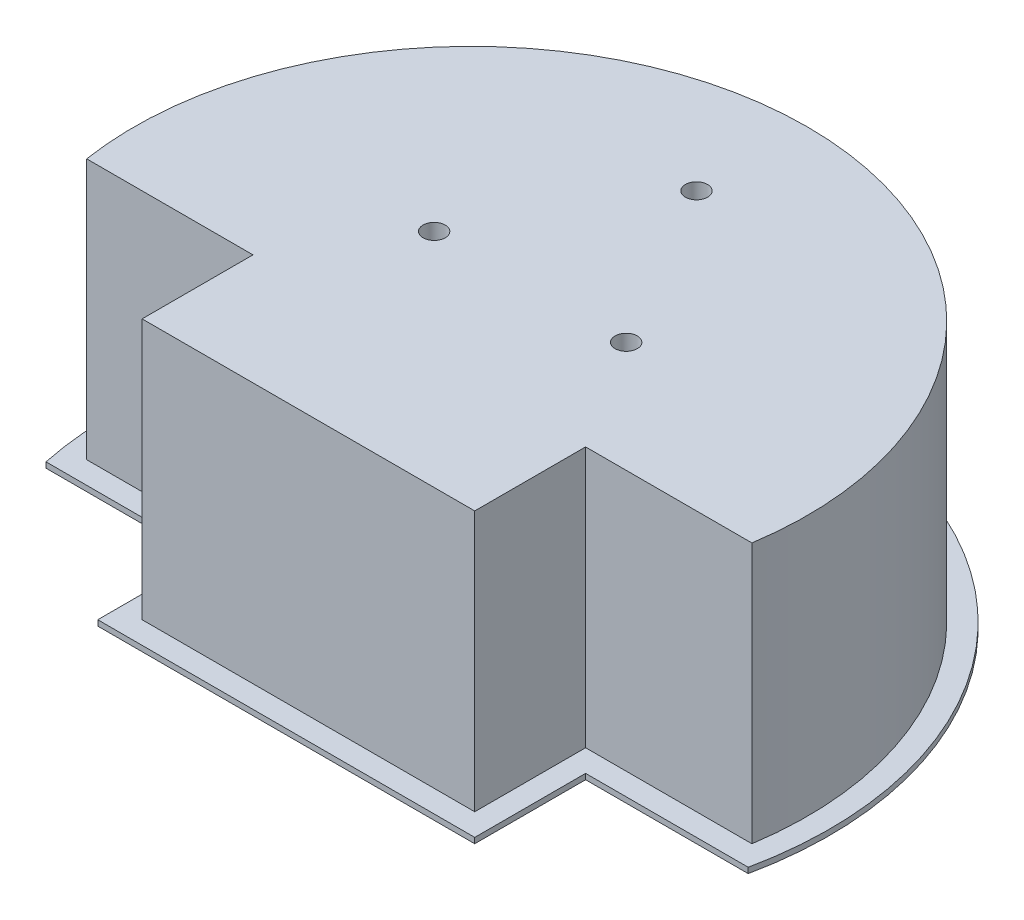
SolidWorks part; units mm, degrees
ref_plane "Alzado" through (0, 0, 0) normal (0, 0, 1) x (1, 0, 0)
ref_plane "Planta" through (0, 0, 0) normal (0, 1, 0) x (1, 0, 0)
ref_plane "Vista lateral" through (0, 0, 0) normal (1, 0, 0) x (0, 0, -1)
sketch "Croquis1" plane through (0, 0, 0) normal (0, 1, 0) x (1, 0, 0)
  line L0 (0, 0) -> (0, 36.4718) construction
  line L1 (-15, 0) -> (15, 0)
  line L2 (-15, 0) -> (-15, 10)
  line L3 (15, 0) -> (15, 10)
  line L4 (-15, 10) -> (-30, 10)
  line L5 (15, 10) -> (30, 10)
  arc A0 (-30, 10) -> (30, 10) centre (0, 14.6429) cw
  point P10 (0, 45)
  dimension "D4" = 35
  dimension "D1" = 30
  dimension "D2" = 10
  dimension "D3" = 15
extrude "Extruir-Lámina1" add sketch "Croquis1" along normal blind 20 thin thin type one direction reverse wall 2
sketch "Croquis2" plane through (0, 20, 0) normal (0, 1, 0) x (1, 0, 0)
  line L0 (15, 10) -> (30, 10) construction
  line L1 (15, 0) -> (15, 10) construction
  line L2 (-15, 0) -> (15, 0) construction
  line L3 (-15, 10) -> (-15, 0) construction
  line L4 (-30, 10) -> (-15, 10) construction
  line L5 (15, 10) -> (30, 10)
  line L6 (15, 0) -> (15, 10)
  line L7 (-15, 0) -> (15, 0)
  line L8 (-15, 10) -> (-15, 0)
  line L9 (-30, 10) -> (-15, 10)
  arc A0 (30, 10) -> (-30, 10) centre (0, 14.6429) ccw construction
  arc A1 (30, 10) -> (-30, 10) centre (0, 14.6429) ccw
extrude "Saliente-Extruir1" add sketch "Croquis2" along normal blind 4
sketch "Croquis3" plane through (0, 20, 0) normal (0, -1, 0) x (1, 0, 0)
  line L0 (0, -20) -> (0, -35) construction
  line L1 (-8.6603, -20) -> (8.6603, -20) construction
  line L2 (8.6603, -20) -> (0, -35) construction
  line L3 (0, -35) -> (-8.6603, -20) construction
  circle A0 centre (-8.6603, -20) radius 2.1
  circle A1 centre (8.6603, -20) radius 2.1
  circle A2 centre (0, -35) radius 2.1
  arc A3 (-30, -10) -> (30, -10) centre (0, -14.6429) ccw construction
  point P11 (0, -45)
  point P12 (0, -27.5)
  dimension "D2" = 4.2
  dimension "D1" = 15
  dimension "D3" = 27.5
extrude "Cortar-Extruir2" cut sketch "Croquis3" against normal blind 2.2
sketch "Croquis4" plane through (0, 0, 0) normal (0, -1, 0) x (1, 0, 0)
  line L0 (17, 2) -> (-17, 2)
  line L1 (-17, 2) -> (-17, -8)
  line L2 (-17, -8) -> (-31.6679, -8)
  line L3 (31.6679, -8) -> (17, -8)
  line L4 (17, -8) -> (17, 2)
  line L6 (13, -12) -> (28.2337, -12) construction
  line L15 (13, -2) -> (13, -12) construction
  line L16 (-13, -2) -> (13, -2) construction
  line L17 (-28.2337, -12) -> (-13, -12) construction
  line L18 (-13, -12) -> (-13, -2) construction
  line L19 (13, -12) -> (28.2337, -12)
  line L20 (13, -2) -> (13, -12)
  line L21 (-13, -2) -> (13, -2)
  line L22 (-28.2337, -12) -> (-13, -12)
  line L23 (-13, -12) -> (-13, -2)
  arc A0 (-31.6679, -8) -> (31.6679, -8) centre (0, -14.6429) ccw
  arc A3 (-28.2337, -12) -> (28.2337, -12) centre (0, -14.6429) ccw construction
  arc A4 (-28.2337, -12) -> (28.2337, -12) centre (0, -14.6429) ccw
extrude "Saliente-Extruir3" add sketch "Croquis4" against normal blind 0.5
sketch "Croquis5" plane through (0, 20, 0) normal (0, -1, 0) x (1, 0, 0)
  circle A0 centre (-8.6603, -20) radius 1
  circle A1 centre (8.6603, -20) radius 1
  circle A2 centre (0, -35) radius 1
  dimension "D1" = 2
extrude "Cortar-Extruir3" cut sketch "Croquis5" against normal blind 10
